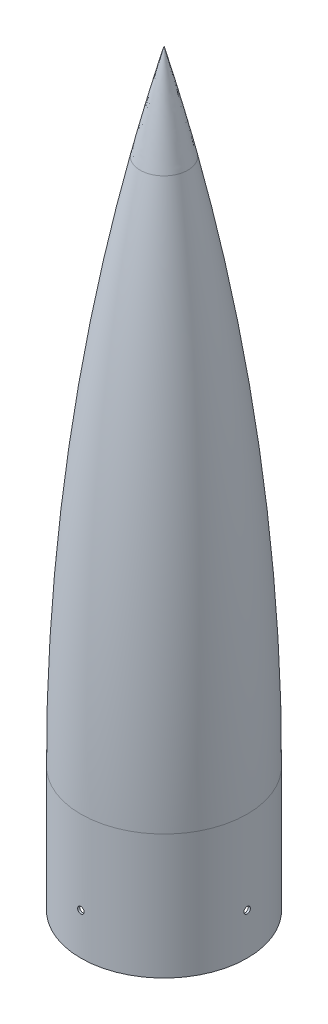
SolidWorks part; units mm, degrees
ref_plane "Front Plane" through (0, 0, 0) normal (0, 0, 1) x (1, 0, 0)
ref_plane "Top Plane" through (0, 0, 0) normal (0, 1, 0) x (1, 0, 0)
ref_plane "Right Plane" through (0, 0, 0) normal (1, 0, 0) x (0, 0, -1)
sketch "Sketch1" plane through (0, 0, 0) normal (0, 0, 1) x (1, 0, 0)
  line L0 (0, 0) -> (0, 457.2) construction
  line L1 (-50.8, 0) -> (-49.53, 0)
  line L2 (-50.8, 0) -> (-50.8, 76.2)
  line L4 (-49.53, 0) -> (-49.53, 76.2)
  line L5 (-13.2665, 398.78) -> (0, 398.78)
  line L6 (0, 457.2) -> (0, 398.78)
  line L7 (-13.2665, 398.78) -> (-14.569, 398.78)
  arc A0 (-50.8, 76.2) -> (0, 457.2) centre (1403.35, 76.2) cw
  arc A1 (-49.53, 76.2) -> (-13.2665, 398.78) centre (1403.35, 76.2) cw
  dimension "D1" = 1.27
  dimension "D2" = 76.2
  dimension "D3" = 50.8
  dimension "D4" = 457.2
  dimension "D5" = 58.42
ref_plane "Plane1" through (0, 457.2, 0) normal (0, 1, 0) x (1, 0, 0)
revolve "Revolve4" add sketch "Sketch1" angle 360 about L0
sketch "Sketch4" plane through (0, 0, 0) normal (0, 0, 1) x (1, 0, 0)
  line L0 (0, 457.2) -> (0, 398.78) construction
  line L1 (0, 457.2) -> (0, 398.78)
  line L3 (14.569, 398.78) -> (-14.569, 398.78) construction
  line L7 (14.569, 398.78) -> (-14.569, 398.78)
  line L8 (0, 398.78) -> (0, 393.4786) construction
  arc A0 (0, 457.2) -> (-50.8, 76.2) centre (1403.35, 76.2) ccw construction
  arc A1 (0, 457.2) -> (-50.8, 76.2) centre (1403.35, 76.2) ccw
revolve "Revolve5" add sketch "Sketch4" angle 360 about L8
extrude "Cut-Extrude1" cut sketch "Sketch5" against normal blind 12.7
sketch "Sketch5" plane through (-80.2742, -85.9656, 50.8) normal (0, 0, 1) x (1, 0, 0)
  circle A0 centre (80.2742, 111.3656) radius 1.9844
  point P2 (0, 0)
pattern_circular "CirPattern1" count 4 over 360 about axis through (0, 0, 0) along (0, -1, 0) of "Cut-Extrude1"
